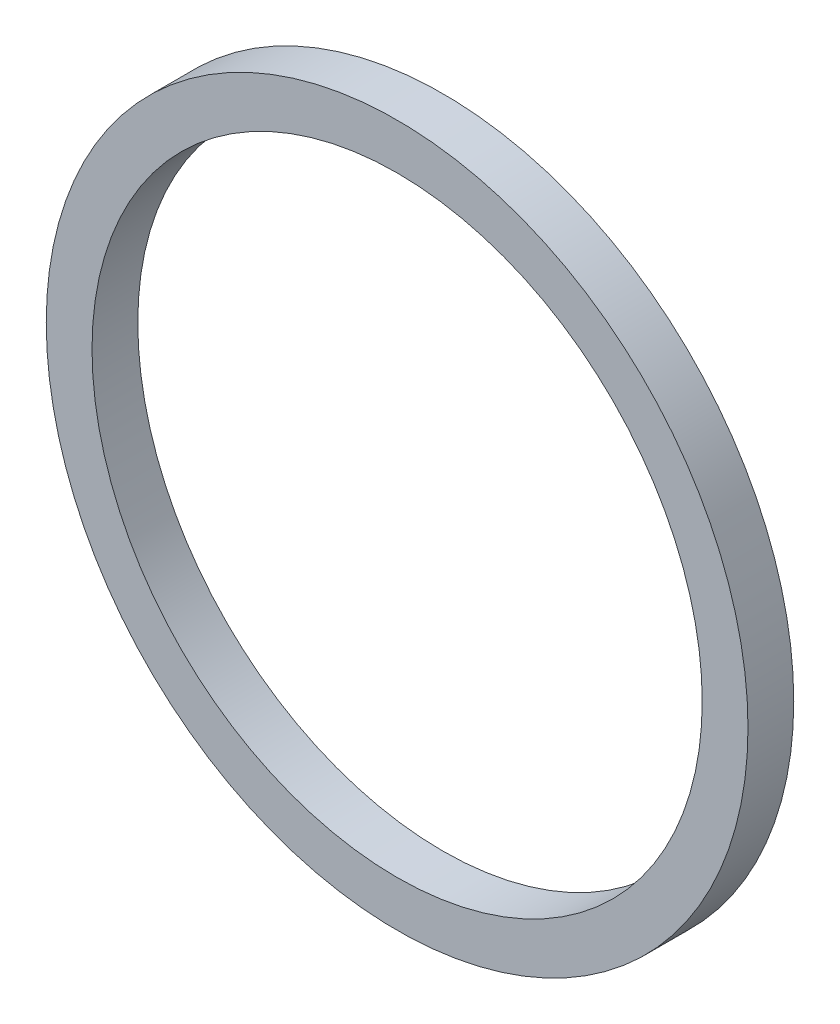
SolidWorks part; units mm, degrees
ref_plane "前视基准面" through (0, 0, 0) normal (0, 0, 1) x (1, 0, 0)
ref_plane "上视基准面" through (0, 0, 0) normal (0, 1, 0) x (1, 0, 0)
ref_plane "右视基准面" through (0, 0, 0) normal (1, 0, 0) x (0, 0, -1)
sketch "草图1" plane through (0, 0, 0) normal (0, 0, 1) x (1, 0, 0)
  circle A0 centre (0, 0) radius 11.5
  circle A1 centre (0, 0) radius 10
  dimension "D1" = 20
  dimension "D2" = 23
extrude "凸台-拉伸1" add sketch "草图1" along normal blind 1.5 contours A0
